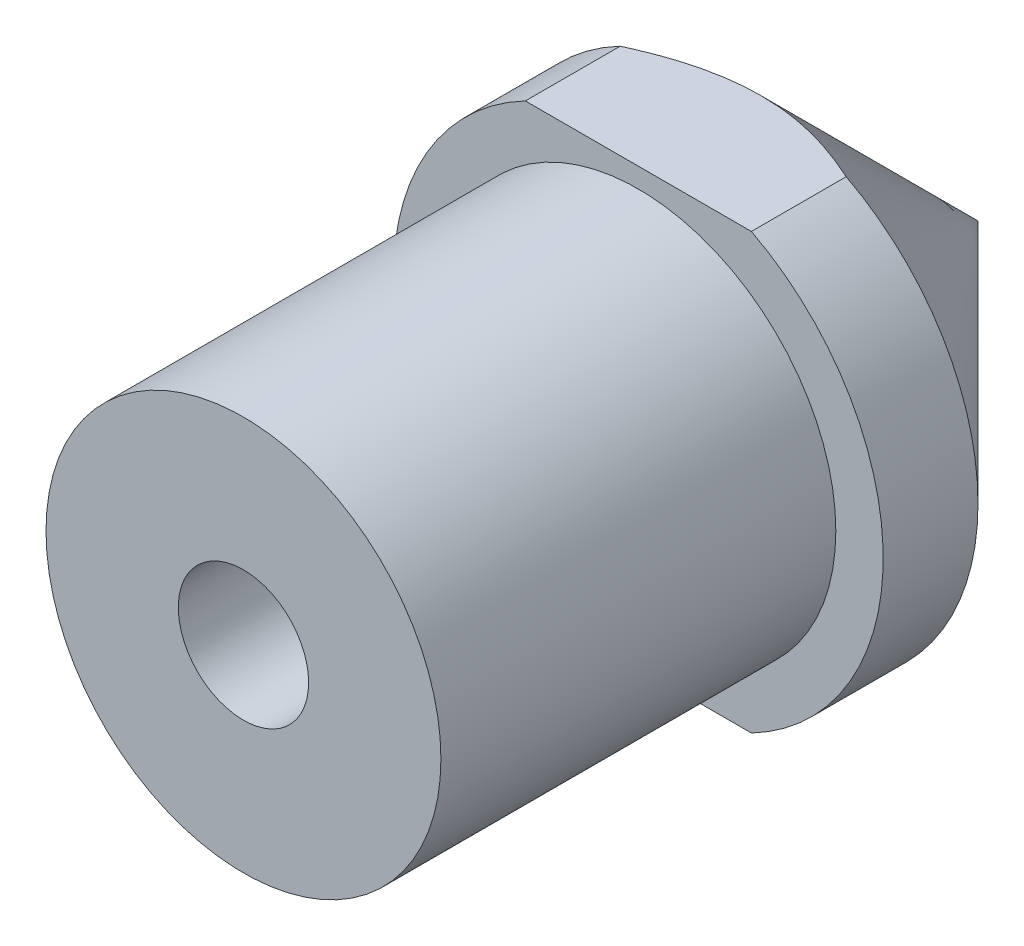
SolidWorks part; units mm, degrees
other "DetailItem3"
ref_plane "Front Plane" through (0, 0, 0) normal (0, 0, 1) x (1, 0, 0)
ref_plane "Top Plane" through (0, 0, 0) normal (0, 1, 0) x (1, 0, 0)
ref_plane "Right Plane" through (0, 0, 0) normal (1, 0, 0) x (0, 0, -1)
sketch "Sketch1" plane through (0, 0, 0) normal (0, 0, 1) x (1, 0, 0)
  circle A0 centre (-22.6644, -3.7026) radius 5
  dimension "D1" = 10
extrude "Boss-Extrude1" add sketch "Sketch1" along normal blind 10
cosmetic thread "Cosmetic Thread2" parameters "D1"=8, "D2"=8.619
cosmetic thread "Cosmetic Thread3" parameters "D1"=8, "D2"=8.619
sketch "Sketch2" plane through (0, 0, 0) normal (0, 0, -1) x (-1, 0, 0)
  line L0 (25.5262, -9.2026) -> (19.8026, -9.2026)
  line L1 (25.5262, 1.7974) -> (19.8026, 1.7974)
  arc A0 (25.5262, -9.2026) -> (25.5262, 1.7974) centre (22.6644, -3.7026) ccw
  arc A1 (19.8026, 1.7974) -> (19.8026, -9.2026) centre (22.6644, -3.7026) ccw
  dimension "D1" = 12.4
  dimension "D2" = 5.5
  dimension "D3" = 5.5
  dimension "D4" = 0
extrude "Boss-Extrude3" add sketch "Sketch2" along normal blind 2.4 contours A0 L1 A1 L0
ref_plane "Plane4" through (0, -3.7026, 0) normal (0, 1, 0) x (1, 0, 0)
sketch "Sketch13" plane through (0, -3.7026, 0) normal (0, 1, 0) x (1, 0, 0)
  line L0 (-22.6644, 2.4) -> (-22.6644, 8.6)
  line L1 (-16.4644, 2.4) -> (-19.8026, 2.4) construction
  line L2 (-22.6644, 8.6) -> (-16.4644, 2.4)
  line L3 (-25.5262, 2.4) -> (-19.8026, 2.4) construction
  line L5 (-22.6644, 8.6) -> (-28.8644, 2.4)
  line L6 (-22.7759, 2.4) -> (-22.6644, 2.4)
  line L7 (-16.4644, 2.4) -> (-22.6644, 2.4)
  dimension "D1" = 90
  dimension "D2" = 45
  dimension "D3" = 45
  dimension "D4" = 0
revolve "Revolve1" add sketch "Sketch13" angle 360 about L0
sketch "Sketch15" plane through (0, 0, -2.4) normal (0, 0, 1) x (1, 0, 0)
  line L1 (-25.5262, 1.7974) -> (-19.4979, 1.7974)
  line L2 (-25.5262, 1.7974) -> (-25.5262, 4.7885)
  line L3 (-25.5262, 4.7885) -> (-19.4979, 4.7885)
  line L4 (-19.4979, 1.7974) -> (-19.4979, 4.7885)
extrude "Cut-Extrude1" cut sketch "Sketch15" against normal blind 2.4
sketch "Sketch16" plane through (0, 0, -2.4) normal (0, 0, 1) x (1, 0, 0)
  line L1 (-19.8026, -9.2026) -> (-26.3934, -9.2026)
  line L2 (-19.8026, -9.2026) -> (-19.8026, -10.294)
  line L3 (-19.8026, -10.294) -> (-26.3934, -10.294)
  line L4 (-26.3934, -9.2026) -> (-26.3934, -10.294)
extrude "Cut-Extrude3" cut sketch "Sketch16" against normal blind 2.4
hole_wizard "M4x0.7 Tapped Hole1" positions "Sketch18" profile "Sketch17" tap size "M4x0.7" standard "ANSI Metric"
sketch "Sketch18" plane through (0, 0, 10) normal (0, 0, 1) x (1, 0, 0)
  circle A0 centre (-22.6644, -3.7026) radius 5 construction
  point P0 (-22.6644, -3.7026)
  dimension "D1" = 0
sketch "Sketch17" plane through (-22.6644, -3.7026, 10) normal (1, 0, 0) x (0, -1, 0)
  line L0 (0, 0) -> (0, 11.0914)
  line L1 (0, 11.0914) -> (1.65, 10.1)
  line L2 (1.65, 10.1) -> (1.65, 0)
  line L5 (1.65, 0) -> (0, 0)
  line L10 (0, 11.0914) -> (-1.65, 10.1) construction
  line L11 (0, -6.35) -> (0, 107.95) construction
  dimension "Tap Drill Dia." = 3.3
  dimension "Tap Drill Depth" = 10.1
  dimension "Drill Angle" = 118
cosmetic thread "Hole Thread1" parameters "D1"=8, "D2"=4
